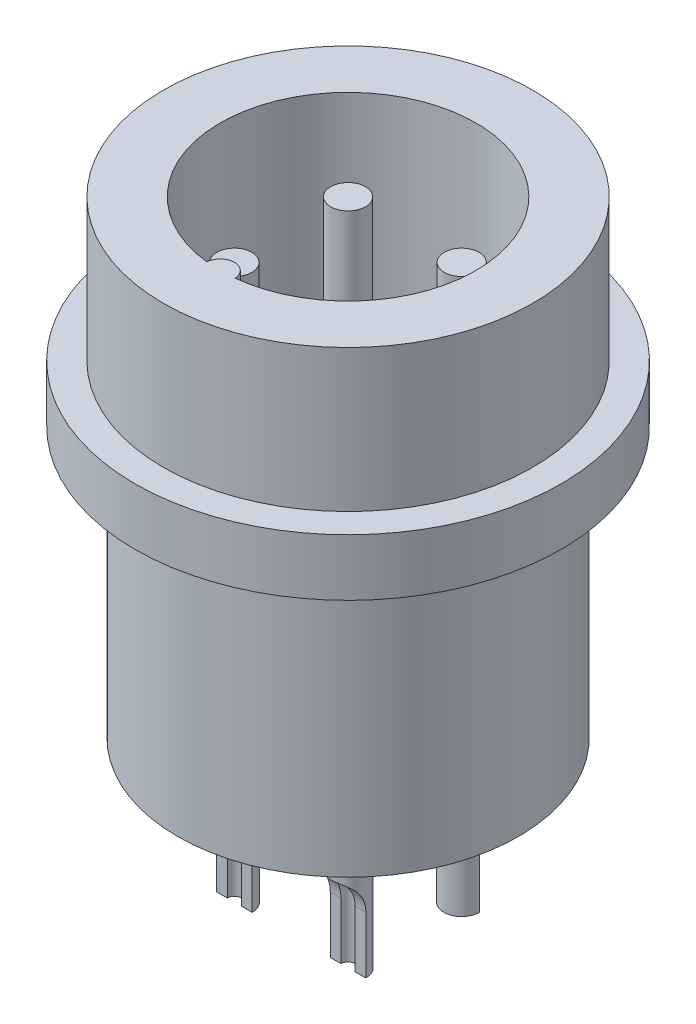
SolidWorks part; units mm, degrees
ref_plane "Спереди" through (0, 0, 0) normal (0, 0, 1) x (1, 0, 0)
ref_plane "Сверху" through (0, 0, 0) normal (0, 1, 0) x (1, 0, 0)
ref_plane "Справа" through (0, 0, 0) normal (1, 0, 0) x (0, 0, -1)
sketch "Эскиз1" plane through (0, 0, 0) normal (0, 1, 0) x (1, 0, 0)
  circle A0 centre (0, 0) radius 6
extrude "Бобышка-Вытянуть1" add sketch "Эскиз1" along normal blind 9.5
sketch "Эскиз2" plane through (0, 9.5, 0) normal (0, 1, 0) x (1, 0, 0)
  circle A0 centre (0, 0) radius 7.5
extrude "Бобышка-Вытянуть2" add sketch "Эскиз2" along normal blind 2
sketch "Эскиз3" plane through (0, 11.5, 0) normal (0, 1, 0) x (1, 0, 0)
  circle A0 centre (0, 0) radius 6.5
extrude "Бобышка-Вытянуть3" add sketch "Эскиз3" along normal blind 5
sketch "Эскиз4" plane through (0, 16.5, 0) normal (0, 1, 0) x (1, 0, 0)
  circle A0 centre (0, 0) radius 4.5
extrude "Вырез-Вытянуть1" cut sketch "Эскиз4" against normal blind 10
sketch "Эскиз5" plane through (0, 6.5, 0) normal (0, 1, 0) x (1, 0, 0)
  arc A0 (-0.4992, -4.4722) -> (0.4992, -4.4722) centre (0, 0) ccw
  arc A1 (0.4992, -4.4722) -> (-0.4992, -4.4722) centre (0, -4.5) ccw
extrude "Бобышка-Вытянуть4" add sketch "Эскиз5" along normal up to surface (10 mm away) up to face at (0, 16.5, 4.5)
sketch "Эскиз6" plane through (0, 6.5, 0) normal (0, 1, 0) x (1, 0, 0)
  line L1 (-2, -2) -> (2, -2) construction
  line L2 (-2, -2) -> (-2, 2) construction
  line L3 (-2, 2) -> (2, 2) construction
  line L4 (2, -2) -> (2, 2) construction
  line L5 (-2, -2) -> (2, 2) construction
  line L6 (-2, 2) -> (2, -2) construction
  circle A0 centre (-2, 2) radius 0.6125
  circle A1 centre (-2, -2) radius 0.6125
  circle A2 centre (2, -2) radius 0.6125
  circle A3 centre (2, 2) radius 0.6125
  point P0 (0, 0)
  dimension "D2" = 1.225
  dimension "D1" = 4
extrude "Бобышка-Вытянуть5" add sketch "Эскиз6" along normal blind 8 contours A2 | A1 | A0 | A3
sketch "Эскиз7" plane through (0, 0, 0) normal (0, -1, 0) x (1, 0, 0)
  line L0 (2, -2) -> (-2, -2) construction
  line L1 (2, 2) -> (-2, 2) construction
  line L2 (2, 2) -> (2, -2) construction
  line L3 (2, -2) -> (-2, -2) construction
  line L4 (-2, 2) -> (-2, -2) construction
  line L5 (2, 2) -> (-2, -2) construction
  line L6 (2, -2) -> (-2, 2) construction
  line L7 (2, -2) -> (2, 2) construction
  circle A0 centre (2, -2) radius 0.625
  circle A3 centre (-2, -2) radius 0.625
  circle A4 centre (-2, 2) radius 0.625
  circle A5 centre (2, 2) radius 0.625
  point P0 (0, 0)
  dimension "D2" = 1.25
  dimension "D1" = 4
  dimension "D5" = 4
  dimension "D6" = 4
  dimension "D3" = 2
  dimension "D4" = 2
extrude "Бобышка-Вытянуть6" add sketch "Эскиз7" along normal blind 5
sketch "Эскиз8" plane through (0, -5, 0) normal (0, -1, 0) x (1, 0, 0)
  line L0 (2, -2) -> (-2, -2) construction
  circle A0 centre (2, -2) radius 0.25
  circle A1 centre (-2, -2) radius 0.25
  circle A2 centre (-2, 2) radius 0.25
  circle A3 centre (2, 2) radius 0.25
  dimension "D1" = 0.5
  dimension "D4" = 4
  dimension "D2" = 2
  dimension "D3" = 2
extrude "Вырез-Вытянуть2" cut sketch "Эскиз8" against normal blind 3
sketch "Эскиз9" plane through (0, 0, 0) normal (1, 0, 0) x (0, 0, -1)
  line L0 (2, -5) -> (2.625, -5)
  line L1 (2.625, -5) -> (2.625, -2)
  line L3 (2, -3) -> (2, -5)
  line L4 (0, 2.4591) -> (0, -8.7527) construction
  line L5 (-2, -5) -> (-2.625, -5)
  line L6 (-2.625, -5) -> (-2.625, -2)
  line L7 (-2, -3) -> (-2, -5)
  arc A0 (2, -3) -> (2.625, -2) centre (3.1125, -3) cw
  arc A1 (-2, -3) -> (-2.625, -2) centre (-3.1125, -3) ccw
  dimension "D1" = 0.625
  dimension "D2" = 3
  dimension "D3" = 2
extrude "Вырез-Вытянуть3" cut sketch "Эскиз9" against normal mid plane 20
